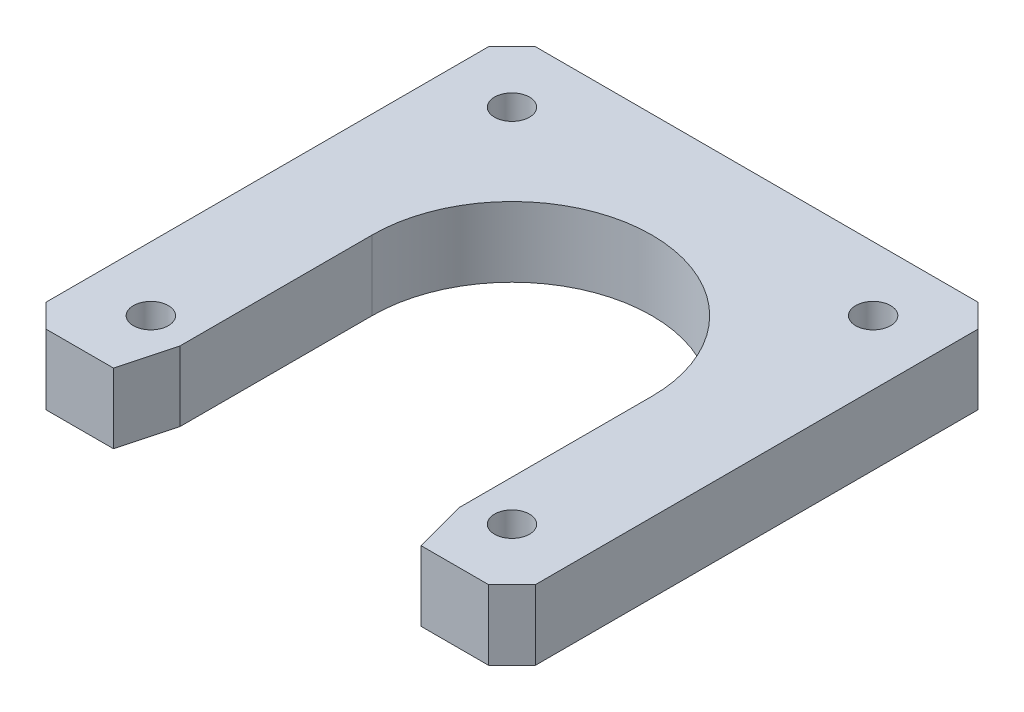
SolidWorks part; units mm, degrees
ref_plane "Front Plane" through (0, 0, 0) normal (0, 0, 1) x (1, 0, 0)
ref_plane "Top Plane" through (0, 0, 0) normal (0, 1, 0) x (1, 0, 0)
ref_plane "Right Plane" through (0, 0, 0) normal (1, 0, 0) x (0, 0, -1)
sketch "Sketch1" plane through (0, 0, 0) normal (0, 1, 0) x (1, 0, 0)
  line L1 (-21, -21) -> (21, -21)
  line L2 (-21, -21) -> (-21, 21)
  line L3 (-21, 21) -> (21, 21)
  line L4 (21, -21) -> (21, 21)
  line L5 (-21, -21) -> (21, 21) construction
  line L6 (-21, 21) -> (21, -21) construction
  line L7 (-15.5, 15.5) -> (15.5, 15.5) construction
  line L8 (-15.5, 15.5) -> (-15.5, -15.5) construction
  line L9 (-15.5, -15.5) -> (15.5, -15.5) construction
  line L10 (15.5, 15.5) -> (15.5, -15.5) construction
  circle A0 centre (0, 0) radius 12
  circle A1 centre (-15.5, 15.5) radius 1.5
  circle A2 centre (15.5, 15.5) radius 1.5
  circle A3 centre (15.5, -15.5) radius 1.5
  circle A4 centre (-15.5, -15.5) radius 1.5
  point P0 (0, 0)
  dimension "D2" = 24
  dimension "D3" = 3
  dimension "D1" = 42
  dimension "D4" = 31
extrude "Boss-Extrude1" add sketch "Sketch1" along normal blind 6
chamfer "Chamfer1" distance 2 angle 45 4 edges at (-21, 3, -21) (21, 3, -21) (21, 3, 21) (-21, 3, 21)
sketch "Sketch2" plane through (0, 6, 0) normal (0, 1, 0) x (1, 0, 0)
  line L0 (-12, 0) -> (-12, -21)
  line L1 (-19, -21) -> (19, -21) construction
  line L2 (-12, -21) -> (12, -21)
  line L3 (12, -21) -> (12, 0)
  line L4 (12, 0) -> (-12, 0)
  circle A0 centre (0, 0) radius 12 construction
extrude "Cut-Extrude1" cut sketch "Sketch2" against normal through all
chamfer "Chamfer2" distance 4.5 angle 15 2 edges at (12, 3, 21) (-12, 3, 21)
equation "\"M3_d\"= 3"
equation "\"housing_t\"= \"housing_t_glob@troublemaker.Assembly\""
equation "\"D3@Sketch1\"=\"M3_d\""
equation "\"D1@Boss-Extrude1\"=\"housing_t\""
